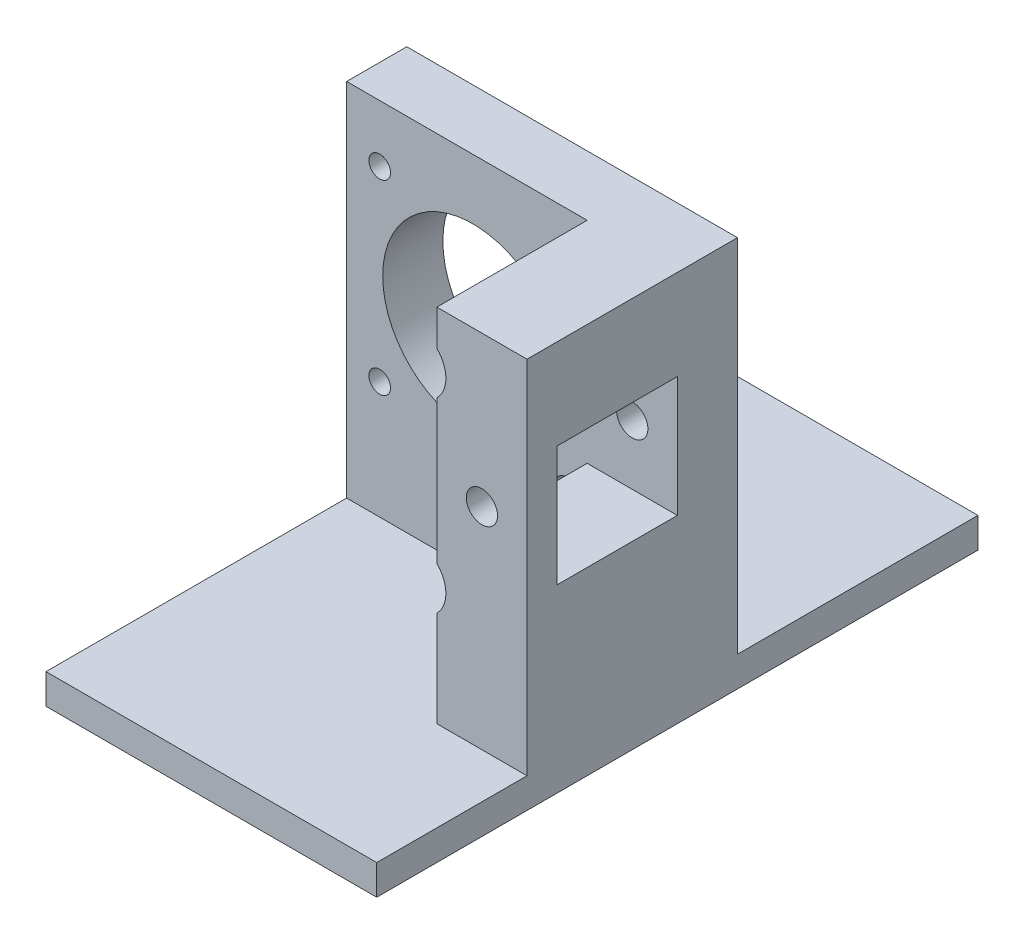
SolidWorks part; units mm, degrees
ref_plane "Front Plane" through (0, 0, 0) normal (0, 0, 1) x (1, 0, 0)
ref_plane "Top Plane" through (0, 0, 0) normal (0, 1, 0) x (1, 0, 0)
ref_plane "Right Plane" through (0, 0, 0) normal (1, 0, 0) x (0, 0, -1)
sketch "Sketch4" plane through (0, 0, 0) normal (0, 1, 0) x (1, 0, 0)
  line L1 (0, 0) -> (40, 0)
  line L2 (0, 0) -> (0, 80)
  line L3 (0, 80) -> (40, 80)
  line L4 (40, 0) -> (40, 80)
  dimension "D1" = 80
  dimension "D2" = 40
extrude "Boss-Extrude4" add sketch "Sketch4" along normal blind 5
sketch "Sketch5" plane through (0, 5, 0) normal (0, 1, 0) x (1, 0, 0)
  line L0 (40, 40) -> (30, 40)
  line L1 (30, 30) -> (30, 50) construction
  line L2 (40, 50) -> (30, 50)
  line L3 (30, 50) -> (30, 55)
  line L4 (0, 80) -> (0, 0)
  line L5 (0, 0) -> (40, 0)
  line L6 (40, 0) -> (40, 80)
  line L7 (40, 80) -> (0, 80)
  line L8 (0, 80) -> (0, 0)
  line L9 (0, 0) -> (40, 0)
  line L10 (40, 0) -> (40, 80)
  line L11 (40, 80) -> (0, 80)
  line L12 (30, 55) -> (40, 55)
  line L13 (40, 55) -> (40, 50)
  line L14 (40, 30) -> (30, 30)
  line L15 (30, 30) -> (30, 25)
  line L16 (30, 25) -> (40, 25)
  line L17 (40, 25) -> (40, 30)
  point P9 (30, 40)
  line M11 (40, 0) -> (40, 80)
  dimension "D2" = 10
  dimension "D3" = 10
  dimension "D4" = 5
  dimension "D5" = 5
  dimension "D1" = 0
extrude "Boss-Extrude6" add sketch "Sketch5" along normal blind 50 contours L12 L3 L2 M11 | L15 L16 L10 L14
sketch "Sketch7" plane through (0, 0, -50) normal (0, 0, 1) x (1, 0, 0)
  line L1 (30, 5) -> (40, 5)
  line L2 (30, 5) -> (30, 30)
  line L3 (30, 30) -> (40, 30)
  line L4 (40, 5) -> (40, 30)
  line L5 (40, 55) -> (40, 5) construction
  line L7 (30, 55) -> (40, 55)
  line L8 (30, 55) -> (30, 50)
  line L9 (30, 50) -> (40, 50)
  line L10 (40, 55) -> (40, 50)
  dimension "D1" = 25
  dimension "D2" = 10
  dimension "D3" = 5
extrude "Boss-Extrude7" add sketch "Sketch7" along normal up to surface (20 mm away) contours L8 L7 L10 L9 | L2 L1 L4 L3 up to face at (35, 30, -30)
sketch "Sketch8" plane through (0, 0, -80) normal (0, 0, -1) x (-1, 0, 0)
  line L4 (-40, 0) -> (0, 0)
  line L5 (0, 0) -> (0, 5)
  line L6 (0, 5) -> (-40, 5)
  line L7 (-40, 5) -> (-40, 0)
  line L8 (-40, 0) -> (0, 0)
  line L9 (0, 0) -> (0, 5)
  line L10 (0, 5) -> (-40, 5)
  line L11 (-40, 5) -> (-40, 0)
  dimension "D1" = 0
extrude "Boss-Extrude8" add sketch "Sketch8" along normal blind 20 contours L8 L9 L10 L11
sketch "Sketch9" plane through (0, 0, 0) normal (-1, 0, 0) x (0, 0, 1)
  line L4 (-100, 0) -> (0, 0)
  line L5 (0, 0) -> (0, 5)
  line L6 (0, 5) -> (-100, 5)
  line L7 (-100, 5) -> (-100, 0)
  line L8 (-100, 0) -> (0, 0)
  line L9 (0, 0) -> (0, 5)
  line L10 (0, 5) -> (-100, 5)
  line L11 (-100, 5) -> (-100, 0)
  dimension "D1" = 0
extrude "Boss-Extrude9" add sketch "Sketch9" along normal blind 10
sketch "Sketch10" plane through (30, 0, 0) normal (-1, 0, 0) x (0, 0, 1)
  line L0 (-25, 5) -> (-55, 5) construction
  line L1 (-55, 55) -> (-50, 55)
  line L2 (-55, 55) -> (-55, 5)
  line L3 (-55, 5) -> (-50, 5)
  line L4 (-50, 55) -> (-50, 5)
  dimension "D1" = 5
extrude "Boss-Extrude10" add sketch "Sketch10" along normal blind 40 contours L2 L1 L4 L3
sketch "Sketch11" plane through (0, 55, 0) normal (0, 1, 0) x (1, 0, 0)
  line L6 (40, 55) -> (-10, 55)
  line L7 (-10, 55) -> (-10, 50)
  line L8 (-10, 50) -> (30, 50)
  line L9 (30, 50) -> (30, 25)
  line L10 (30, 25) -> (40, 25)
  line L11 (40, 25) -> (40, 55)
  line L12 (40, 55) -> (-10, 55)
  line L13 (-10, 55) -> (-10, 50)
  line L14 (-10, 50) -> (30, 50)
  line L15 (30, 50) -> (30, 25)
  line L16 (30, 25) -> (40, 25)
  line L17 (40, 25) -> (40, 55)
  dimension "D1" = 0
extrude "Boss-Extrude11" add sketch "Sketch11" along normal blind 10
sketch "Sketch12" plane through (0, 0, -50) normal (0, 0, 1) x (1, 0, 0)
  line L0 (30, 50) -> (30, 30)
  line L1 (30, 40) -> (26, 40)
  line L2 (0.3934, 50.6066) -> (-3.227, 54.227)
  line L3 (-10, 61) -> (32, 61)
  line L4 (-10, 61) -> (-10, 19)
  line L5 (-10, 19) -> (32, 19)
  line L6 (32, 61) -> (32, 19)
  line L7 (-10, 61) -> (32, 19) construction
  line L8 (30, 30) -> (40, 30)
  line L9 (40, 30) -> (40, 50)
  line L10 (40, 50) -> (30, 50)
  line L11 (30, 50) -> (30, 65)
  line L12 (30, 65) -> (-10, 65)
  line L13 (-10, 65) -> (-10, 5)
  line L14 (-10, 5) -> (30, 5)
  line L15 (30, 5) -> (30, 30)
  line L16 (30, 30) -> (40, 30)
  line L17 (40, 30) -> (40, 50)
  line L18 (40, 50) -> (30, 50)
  line L19 (30, 50) -> (30, 65)
  line L20 (30, 65) -> (-10, 65)
  line L21 (-10, 65) -> (-10, 5)
  line L22 (-10, 5) -> (30, 5)
  line L23 (30, 5) -> (30, 30)
  line L24 (-10, 19) -> (32, 61) construction
  line L25 (-2.6998, 24.5002) -> (-4.4998, 24.5002) construction
  line L26 (24.6998, 24.5002) -> (-2.6998, 24.5002)
  line L27 (26.4998, 26.3002) -> (26.4998, 53.6998)
  line L28 (24.6998, 55.4998) -> (-2.6998, 55.4998)
  line L29 (-4.4998, 26.3002) -> (-4.4998, 53.6998)
  line L30 (26.4998, 24.5002) -> (-4.4998, 55.4998) construction
  line L31 (26.4998, 55.4998) -> (-4.4998, 24.5002) construction
  line L32 (26.4998, 24.5002) -> (24.6998, 24.5002) construction
  line L33 (26.4998, 24.5002) -> (26.4998, 26.3002) construction
  line L34 (26.4998, 53.6998) -> (26.4998, 55.4998) construction
  line L35 (26.4998, 55.4998) -> (24.6998, 55.4998) construction
  line L36 (11, 40) -> (0.3934, 50.6066) construction
  line L37 (26, 40) -> (11, 40) construction
  line L38 (-3.227, 54.227) -> (-4.4998, 55.4998) construction
  line L39 (-4.4998, 53.6998) -> (-4.4998, 55.4998) construction
  line L40 (-2.6998, 55.4998) -> (-4.4998, 55.4998) construction
  line L41 (-4.4998, 24.5002) -> (-4.4998, 26.3002) construction
  circle A0 centre (11, 40) radius 15
  circle A1 centre (-4.4998, 55.4998) radius 1.8
  circle A2 centre (26.4998, 55.4998) radius 1.8
  circle A3 centre (26.4998, 24.5002) radius 1.8
  circle A4 centre (-4.4998, 24.5002) radius 1.8
  dimension "D2" = 19
  dimension "D3" = 30
  dimension "D6" = 3.6
  dimension "D7" = 3.6
  dimension "D1" = 0
  dimension "D4" = 42
  dimension "D5" = 21.92
extrude "Cut-Extrude1" cut sketch "Sketch12" against normal up to surface (5 mm away) contours A0 | A1 | A2 | A4 | A3 up to face at (15, 35, -55)
sketch "Sketch13" plane through (0, 0, -50) normal (0, 0, 1) x (1, 0, 0)
  line L0 (40, 40) -> (35, 40) construction
  line L8 (30, 30) -> (40, 30)
  line L9 (40, 30) -> (40, 50)
  line L10 (40, 50) -> (30, 50)
  line L11 (30, 50) -> (30, 65)
  line L12 (30, 65) -> (-10, 65)
  line L13 (-10, 65) -> (-10, 5)
  line L14 (-10, 5) -> (30, 5)
  line L15 (30, 5) -> (30, 30)
  line L16 (30, 30) -> (40, 30)
  line L17 (40, 30) -> (40, 50)
  line L18 (40, 50) -> (30, 50)
  line L19 (30, 50) -> (30, 65)
  line L20 (30, 65) -> (-10, 65)
  line L21 (-10, 65) -> (-10, 5)
  line L22 (-10, 5) -> (30, 5)
  line L23 (30, 5) -> (30, 30)
  circle A0 centre (35, 40) radius 2.25
  dimension "D3" = 4.5
  dimension "D2" = 5
  dimension "D1" = 0
extrude "Cut-Extrude2" cut sketch "Sketch13" against normal through all both and the other way through all contours A0
sketch "Sketch14" plane through (0, 0, -25) normal (0, 0, 1) x (1, 0, 0)
  circle A0 centre (35, 40) radius 2.25 construction
  circle A1 centre (35, 40) radius 2.25
  circle A2 centre (35, 40) radius 4
  dimension "D1" = 8
extrude "Cut-Extrude4" cut sketch "Sketch14" against normal blind 2 contours A1 | A2
sketch "Sketch15" plane through (0, 0, -55) normal (0, 0, -1) x (-1, 0, 0)
  circle A0 centre (-35, 40) radius 2.25 construction
  circle A1 centre (-35, 40) radius 2.25
  circle A2 centre (-35, 40) radius 4
  dimension "D1" = 8
extrude "Cut-Extrude5" cut sketch "Sketch15" against normal blind 2
sketch "Sketch17" plane through (0, 0, -25) normal (0, 0, 1) x (1, 0, 0)
  line L0 (26.4998, 55.4998) -> (26.4998, 24.5002)
  circle A0 centre (26.4998, 55.4998) radius 1.8 construction
  circle A1 centre (26.4998, 55.4998) radius 1.8
  circle A2 centre (26.4998, 55.4998) radius 5
  circle A3 centre (26.4998, 24.5002) radius 5
  dimension "D1" = 10
  dimension "D2" = 10
extrude "Cut-Extrude6" cut sketch "Sketch17" against normal up to surface (25 mm away) up to face at (37.25, 40, -50)
sketch "Sketch19" plane through (0, 0, -55) normal (0, 0, -1) x (-1, 0, 0)
  line L4 (10, 5) -> (10, 65)
  line L5 (10, 65) -> (-40, 65)
  line L6 (-40, 65) -> (-40, 5)
  line L7 (-40, 5) -> (10, 5)
  line L8 (10, 5) -> (10, 65)
  line L9 (10, 65) -> (-40, 65)
  line L10 (-40, 65) -> (-40, 5)
  line L11 (-40, 5) -> (10, 5)
  circle A0 centre (4.4998, 55.4998) radius 1.8 construction
  circle A1 centre (4.4998, 24.5002) radius 1.8 construction
  circle A2 centre (-26.4998, 24.5002) radius 1.8 construction
  circle A3 centre (-11, 40) radius 15 construction
  circle A4 centre (-35, 40) radius 4 construction
  circle A6 centre (-26.4998, 55.4998) radius 1.8 construction
  circle A7 centre (4.4998, 55.4998) radius 1.8
  circle A8 centre (4.4998, 24.5002) radius 1.8
  circle A9 centre (-26.4998, 24.5002) radius 1.8
  circle A10 centre (-11, 40) radius 15
  circle A11 centre (-35, 40) radius 4
  circle A13 centre (-26.4998, 55.4998) radius 1.8
  dimension "D1" = 0
extrude "Boss-Extrude13" add sketch "Sketch19" along normal blind 5
sketch "Sketch20" plane through (0, 0, -53) normal (0, 0, -1) x (-1, 0, 0)
  circle A0 centre (-35, 40) radius 2.25 construction
  circle A1 centre (-35, 40) radius 4
  circle A2 centre (-35, 40) radius 4
  circle A3 centre (-35, 40) radius 2.25
  dimension "D1" = 0
extrude "Boss-Extrude14" add sketch "Sketch20" along normal blind 5
sketch "Sketch21" plane through (40, 0, 0) normal (1, 0, 0) x (0, 0, -1)
  line L0 (50, 50) -> (50, 30) construction
  line L1 (30, 50) -> (30, 30) construction
  line L2 (30, 50) -> (50, 50) construction
  line L3 (30, 30) -> (50, 30) construction
  line L4 (50, 50) -> (50, 30)
  line L5 (30, 50) -> (30, 30)
  line L6 (30, 50) -> (50, 50)
  line L7 (30, 30) -> (50, 30)
  line L8 (100, 5) -> (60, 5)
  line L9 (60, 5) -> (60, 65)
  line L10 (60, 65) -> (25, 65)
  line L11 (25, 65) -> (25, 5)
  line L12 (25, 5) -> (0, 5)
  line L13 (0, 5) -> (0, 0)
  line L14 (0, 0) -> (100, 0)
  line L15 (100, 0) -> (100, 5)
  line L16 (100, 5) -> (60, 5)
  line L17 (60, 5) -> (60, 65)
  line L18 (60, 65) -> (25, 65)
  line L19 (25, 65) -> (25, 5)
  line L20 (25, 5) -> (0, 5)
  line L21 (0, 5) -> (0, 0)
  line L22 (0, 0) -> (100, 0)
  line L23 (100, 0) -> (100, 5)
  dimension "D1" = 0
extrude "Boss-Extrude15" add sketch "Sketch21" along normal blind 5
sketch "Sketch22" plane through (0, 0, -60) normal (0, 0, -1) x (-1, 0, 0)
  circle A0 centre (-35, 40) radius 4 construction
  circle A1 centre (-35, 40) radius 4
extrude "Boss-Extrude16" add sketch "Sketch22" against normal up to surface (10 mm away) up to face at (26.0833, 38.3333, -50)
sketch "Sketch23" plane through (0, 0, -25) normal (0, 0, 1) x (1, 0, 0)
  circle A0 centre (35, 40) radius 4 construction
  circle A1 centre (35, 40) radius 4
extrude "Boss-Extrude17" add sketch "Sketch23" against normal up to surface (5 mm away) up to face at (37.25, 40, -30)
sketch "Sketch24" plane through (0, 0, -30) normal (0, 0, -1) x (-1, 0, 0)
  line L0 (-30, 30) -> (-45, 50) construction
  line L1 (-30, 50) -> (-45, 30) construction
  line L4 (-30, 50) -> (-45, 50)
  line L5 (-45, 50) -> (-45, 30)
  line L6 (-45, 30) -> (-30, 30)
  line L7 (-30, 30) -> (-30, 50)
  line L8 (-30, 50) -> (-45, 50)
  line L9 (-45, 50) -> (-45, 30)
  line L10 (-45, 30) -> (-30, 30)
  line L11 (-30, 30) -> (-30, 50)
  circle A0 centre (-37.5, 40) radius 2.6
  dimension "D2" = 5.2
  dimension "D1" = 0
extrude "Cut-Extrude7" cut sketch "Sketch24" against normal through all both and the other way through all contours A0
